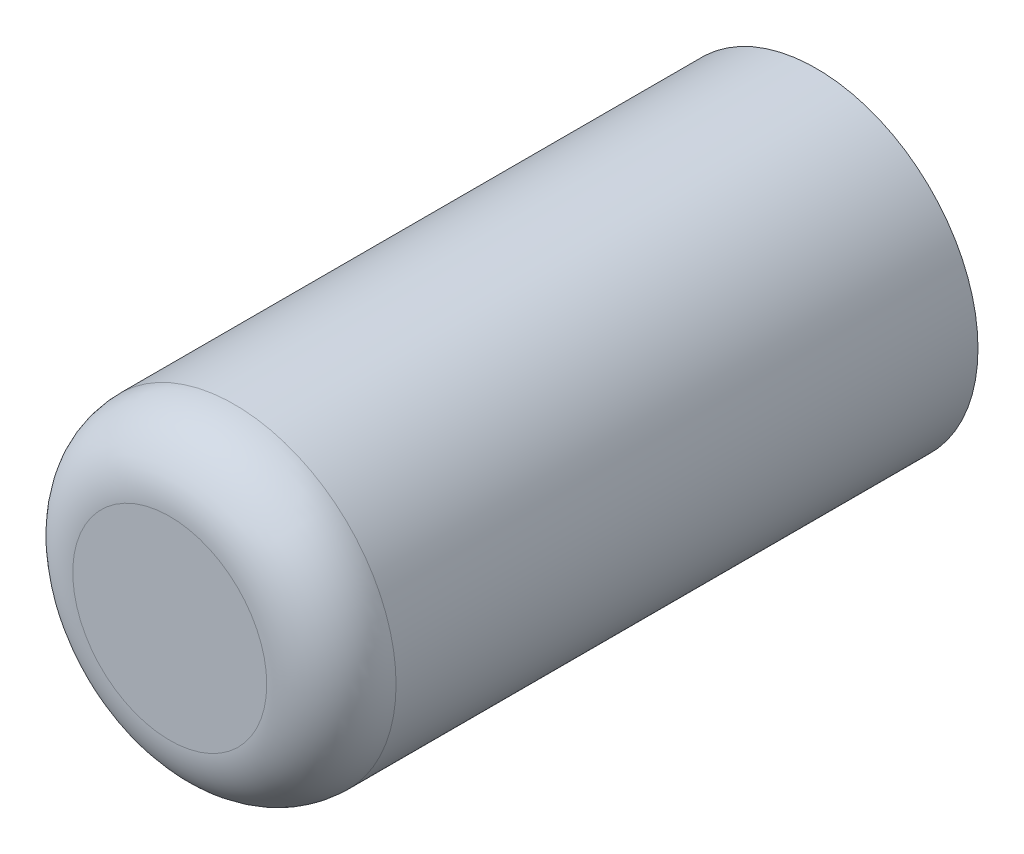
SolidWorks part; units mm, degrees
ref_plane "Спереди" through (0, 0, 0) normal (0, 0, 1) x (1, 0, 0)
ref_plane "Сверху" through (0, 0, 0) normal (0, 1, 0) x (1, 0, 0)
ref_plane "Справа" through (0, 0, 0) normal (1, 0, 0) x (0, 0, -1)
sketch "Эскиз1" plane through (0, 0, 0) normal (0, 0, 1) x (1, 0, 0)
  circle A0 centre (0, 0) radius 25
  dimension "D1" = 50
extrude "Бобышка-Вытянуть1" add sketch "Эскиз1" along normal blind 100
fillet "Скругление1" radius 10 1 edges at (25, 0, 100)
